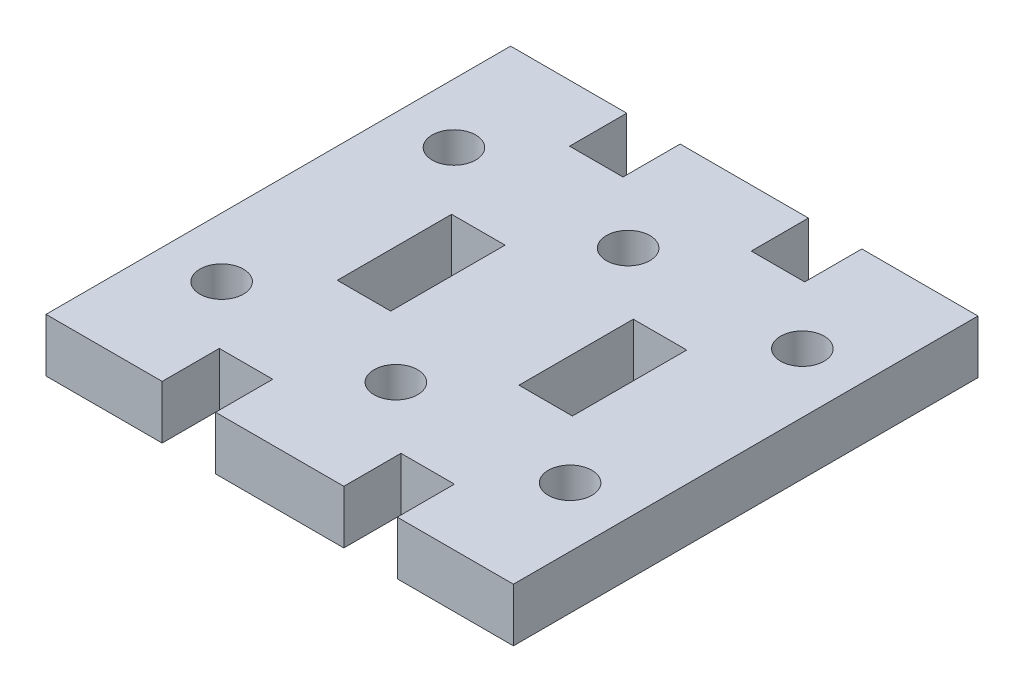
SolidWorks part; units mm, degrees
ref_plane "Front Plane" through (0, 0, 0) normal (0, 0, 1) x (1, 0, 0)
ref_plane "Top Plane" through (0, 0, 0) normal (0, 1, 0) x (1, 0, 0)
ref_plane "Right Plane" through (0, 0, 0) normal (1, 0, 0) x (0, 0, -1)
sketch "Sketch1" plane through (0, 0, 0) normal (0, 1, 0) x (1, 0, 0)
  line L0 (7.212, 0) -> (-7.012, 0) construction
  line L1 (7.012, -25.4) -> (-7.012, -25.4)
  line L2 (7.012, -25.4) -> (7.012, -19.15)
  line L3 (7.012, 25.4) -> (-7.012, 25.4)
  line L4 (-7.012, -25.4) -> (-7.012, -19.15)
  line L5 (7.012, -25.4) -> (-7.012, 25.4) construction
  line L6 (7.012, 25.4) -> (-7.012, -25.4) construction
  line L7 (0, -25.4) -> (0, 25.4) construction
  line L8 (-7.012, 19.15) -> (-7.012, 25.4)
  line L9 (-12.854, 6.25) -> (-7.012, 6.25)
  line L11 (-12.854, 19.15) -> (-7.012, 19.15)
  line L12 (-12.854, -19.15) -> (-7.012, -19.15)
  line L13 (-12.854, 6.25) -> (-7.012, 19.15) construction
  line L14 (-12.854, 19.15) -> (-7.012, 6.25) construction
  line L16 (-12.854, -6.25) -> (-7.012, -6.25)
  line L17 (-7.012, -6.25) -> (-7.012, 6.25)
  line L18 (12.854, -19.15) -> (7.012, -19.15)
  line L19 (12.854, -6.25) -> (12.854, 6.25)
  line L20 (12.854, -6.25) -> (7.012, -6.25)
  line L21 (12.854, 6.25) -> (7.012, 6.25)
  line L22 (12.854, 19.15) -> (12.854, 25.4)
  line L23 (12.854, 19.15) -> (7.012, 19.15)
  line L24 (7.012, -6.25) -> (7.012, 6.25)
  line L25 (7.012, 19.15) -> (7.012, 25.4)
  line L26 (-25.554, -25.4) -> (-12.854, -25.4)
  line L27 (25.554, -25.4) -> (12.854, -25.4)
  line L28 (25.554, -25.4) -> (25.554, 25.4)
  line L29 (25.554, 25.4) -> (12.854, 25.4)
  line L30 (12.854, -25.4) -> (12.854, -19.15)
  line L31 (25.554, -25.4) -> (12.854, 25.4) construction
  line L32 (25.554, 25.4) -> (12.854, -25.4) construction
  line L33 (-12.854, -25.4) -> (-12.854, -19.15)
  line L34 (-12.854, -6.25) -> (-12.854, 6.25)
  line L35 (-12.854, 19.15) -> (-12.854, 25.4)
  line L36 (-25.554, -25.4) -> (-25.554, 25.4)
  line L37 (-25.554, 25.4) -> (-12.854, 25.4)
  point P0 (0, 0)
  point P10 (-9.933, 12.7)
  point P27 (19.204, 0)
  dimension "D1" = 14.024
  dimension "D2" = 50.8
  dimension "D3" = 5.842
  dimension "D4" = 12.9
  dimension "D5" = 12.7
  dimension "D6" = 12.7
extrude "Boss-Extrude1" add sketch "Sketch1" along normal blind 5.842
sketch "Sketch2" plane through (0, 5.842, 0) normal (0, 1, 0) x (1, 0, 0)
  line L0 (0, -25.4) -> (0, 25.4) construction
  line L1 (-7.012, -25.4) -> (7.012, -25.4) construction
  line L2 (7.012, 25.4) -> (-7.012, 25.4) construction
  line L3 (-7.012, 0) -> (7.012, 0) construction
  line L4 (-7.012, 6.25) -> (-7.012, -6.25) construction
  line L5 (7.012, -6.25) -> (7.012, 6.25) construction
  line L6 (25.554, 12.7) -> (-25.554, 12.7) construction
  line L7 (25.554, -25.4) -> (25.554, 25.4) construction
  line L8 (-25.554, 25.4) -> (-25.554, -25.4) construction
  line L9 (25.554, -12.7) -> (-25.554, -12.7) construction
  circle A0 centre (0, -12.7) radius 2.3812
  circle A1 centre (0, 12.7) radius 2.3812
  circle A2 centre (19.05, 12.7) radius 2.3813
  circle A3 centre (19.05, -12.7) radius 2.3813
  circle A4 centre (-19.05, 12.7) radius 2.3813
  circle A5 centre (-19.05, -12.7) radius 2.3813
  dimension "D1" = 4.7625
  dimension "D3" = 4.7625
  dimension "D2" = 12.7
  dimension "D4" = 19.05
extrude "Cut-Extrude1" cut sketch "Sketch2" against normal through all
sketch "Sketch3" plane through (0, 5.842, 0) normal (0, 1, 0) x (1, 0, 0)
  line L0 (0, 25.4) -> (0, -25.4) construction
  line L1 (25.554, 25.4) -> (12.854, 25.4)
  line L2 (25.554, 25.4) -> (25.554, 31.242)
  line L3 (25.554, 31.242) -> (12.854, 31.242)
  line L4 (12.854, 25.4) -> (12.854, 31.242)
  line L5 (7.012, 25.4) -> (-7.012, 25.4) construction
  line L6 (-7.012, -25.4) -> (7.012, -25.4) construction
  line L7 (25.554, 0) -> (-25.554, 0) construction
  line L8 (25.554, -25.4) -> (25.554, 25.4) construction
  line L9 (-25.554, 25.4) -> (-25.554, -25.4) construction
  line L10 (12.854, -25.4) -> (12.854, -31.242)
  line L11 (25.554, -31.242) -> (12.854, -31.242)
  line L12 (25.554, -25.4) -> (25.554, -31.242)
  line L13 (25.554, -25.4) -> (12.854, -25.4)
  line L14 (-25.554, -25.4) -> (-12.854, -25.4)
  line L15 (-25.554, -25.4) -> (-25.554, -31.242)
  line L16 (-25.554, -31.242) -> (-12.854, -31.242)
  line L17 (-12.854, -25.4) -> (-12.854, -31.242)
  line L18 (-12.854, 25.4) -> (-12.854, 31.242)
  line L19 (-25.554, 31.242) -> (-12.854, 31.242)
  line L20 (-25.554, 25.4) -> (-25.554, 31.242)
  line L21 (-25.554, 25.4) -> (-12.854, 25.4)
  dimension "D1" = 5.842
  dimension "D2" = 12.7
extrude "Boss-Extrude2" [suppressed] add sketch "Sketch3" against normal up to surface (5.842 mm away)
fillet "Fillet1" [suppressed] radius 3.175
